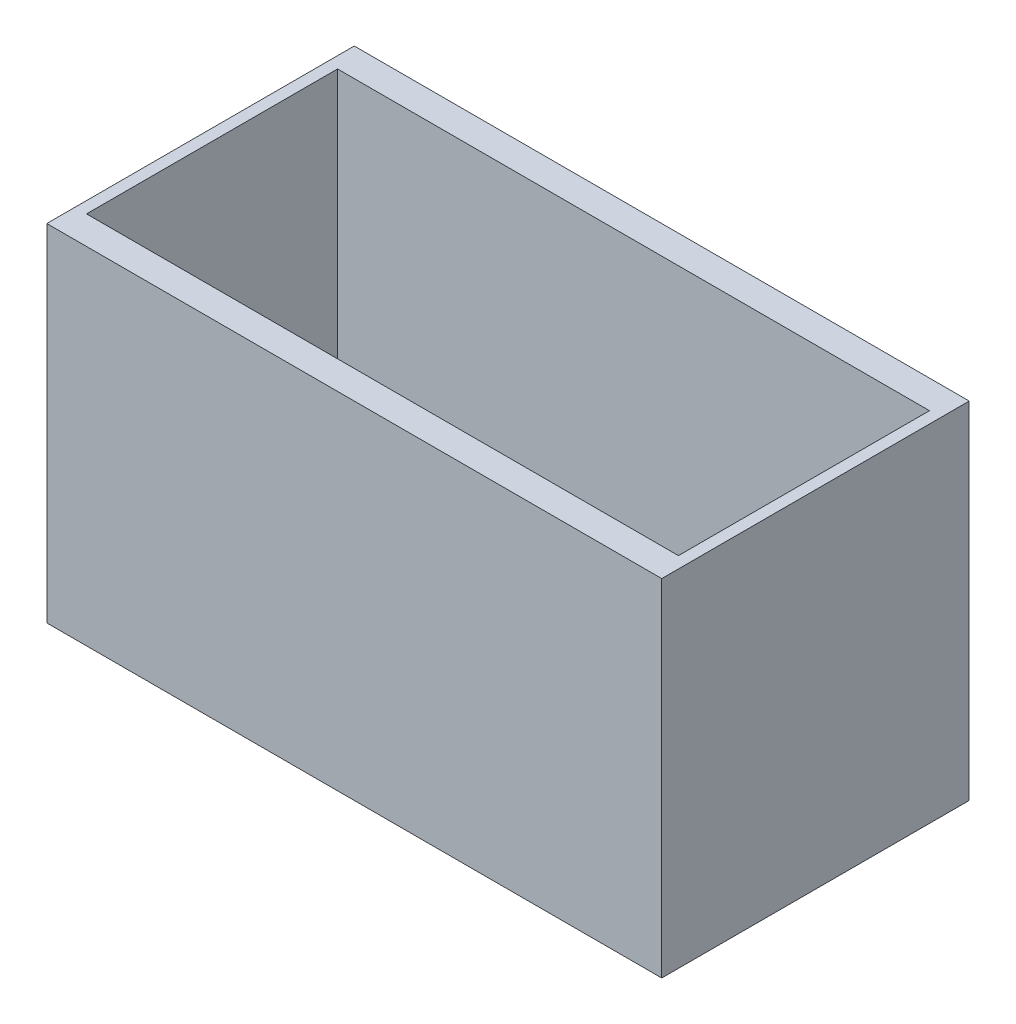
SolidWorks part; units mm, degrees
ref_plane "Front Plane" through (0, 0, 0) normal (0, 0, 1) x (1, 0, 0)
ref_plane "Top Plane" through (0, 0, 0) normal (0, 1, 0) x (1, 0, 0)
ref_plane "Right Plane" through (0, 0, 0) normal (1, 0, 0) x (0, 0, -1)
sketch "Sketch1" plane through (0, 0, 0) normal (0, 1, 0) x (1, 0, 0)
  line L1 (-40, -20) -> (40, -20)
  line L2 (-40, -20) -> (-40, 20)
  line L3 (-40, 20) -> (40, 20)
  line L4 (40, -20) -> (40, 20)
  line L5 (-40, -20) -> (40, 20) construction
  line L6 (-40, 20) -> (40, -20) construction
  point P0 (0, 0)
  dimension "D1" = 80
  dimension "D2" = 40
extrude "Boss-Extrude1" add sketch "Sketch1" along normal blind 45
sketch "Sketch2" plane through (0, 45, 0) normal (0, 1, 0) x (1, 0, 0)
  line L1 (-38.5, -16.3286) -> (38.5, -16.3286)
  line L2 (-38.5, -16.3286) -> (-38.5, 16.3286)
  line L3 (-38.5, 16.3286) -> (38.5, 16.3286)
  line L4 (38.5, -16.3286) -> (38.5, 16.3286)
  line L5 (-38.5, -16.3286) -> (38.5, 16.3286) construction
  line L6 (-38.5, 16.3286) -> (38.5, -16.3286) construction
  point P0 (0, 0)
  dimension "D1" = 77
extrude "Cut-Extrude1" cut sketch "Sketch2" against normal blind 44
